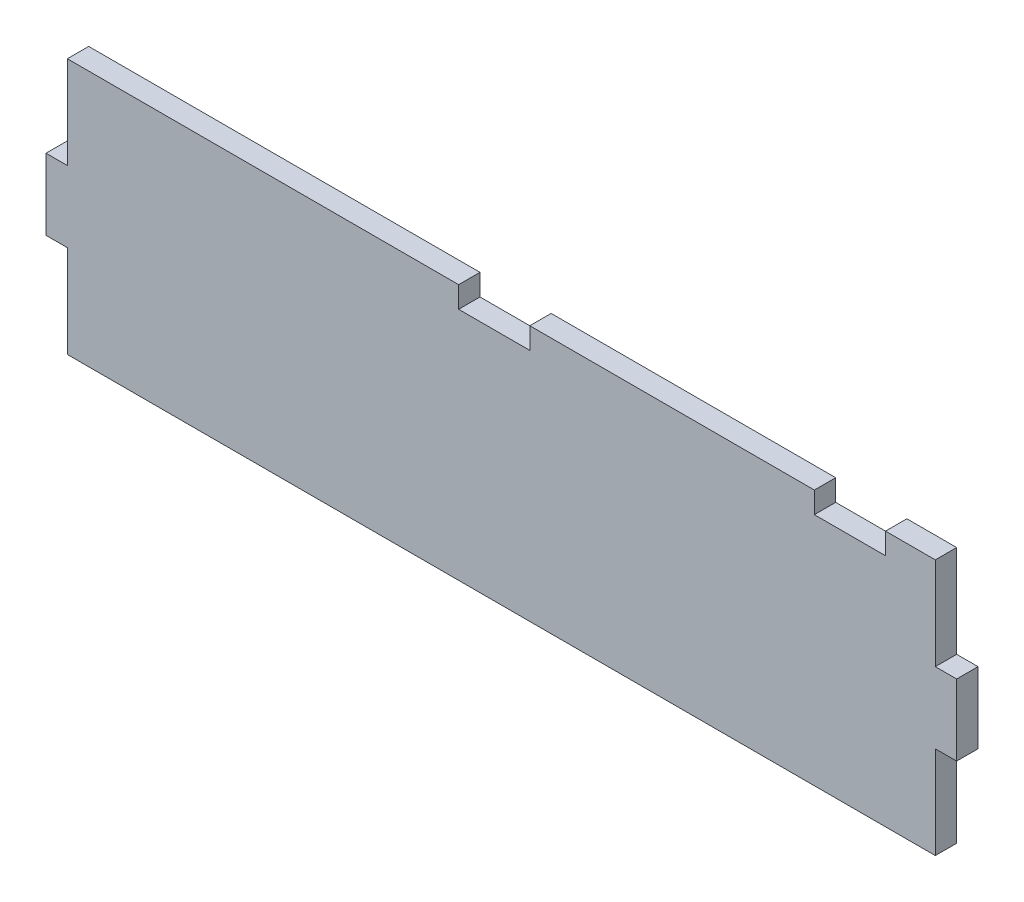
SolidWorks part; units mm, degrees
ref_plane "Спереди" through (0, 0, 0) normal (0, 0, 1) x (1, 0, 0)
ref_plane "Сверху" through (0, 0, 0) normal (0, 1, 0) x (1, 0, 0)
ref_plane "Справа" through (0, 0, 0) normal (1, 0, 0) x (0, 0, -1)
sketch "Эскиз1" plane through (0, 0, 0) normal (0, 0, 1) x (1, 0, 0)
  line L0 (0, 0) -> (0, 26)
  line L1 (0, 0) -> (244, 0)
  line L4 (244, 0) -> (244, 26)
  line L5 (0, 26) -> (-6, 26)
  line L6 (-6, 26) -> (-6, 46)
  line L7 (-6, 46) -> (0, 46)
  line L9 (210, 66) -> (230, 66)
  line L10 (244, 26) -> (250, 26)
  line L11 (250, 26) -> (250, 46)
  line L12 (250, 46) -> (244, 46)
  line L13 (244, 46) -> (244, 66)
  line L14 (110, 72) -> (0, 72)
  line L17 (110, 72) -> (110, 66)
  line L18 (0, 72) -> (0, 46)
  line L19 (130, 66) -> (130, 72)
  line L20 (130, 72) -> (210, 72)
  line L21 (210, 72) -> (210, 66)
  line L23 (230, 66) -> (230, 72)
  line L24 (230, 72) -> (244, 72)
  line L25 (244, 72) -> (244, 66)
  line L26 (110, 66) -> (130, 66)
  dimension "D1" = 244
  dimension "D2" = 66
  dimension "D3" = 110
  dimension "D4" = 6
  dimension "D5" = 20
  dimension "D6" = 26
  dimension "D7" = 26
  dimension "D8" = 14
  dimension "D9" = 20
  dimension "D10" = 80
  dimension "D11" = 20
  dimension "D12" = 6
  dimension "D13" = 6
extrude "Бобышка-Вытянуть1" add sketch "Эскиз1" along normal blind 6
